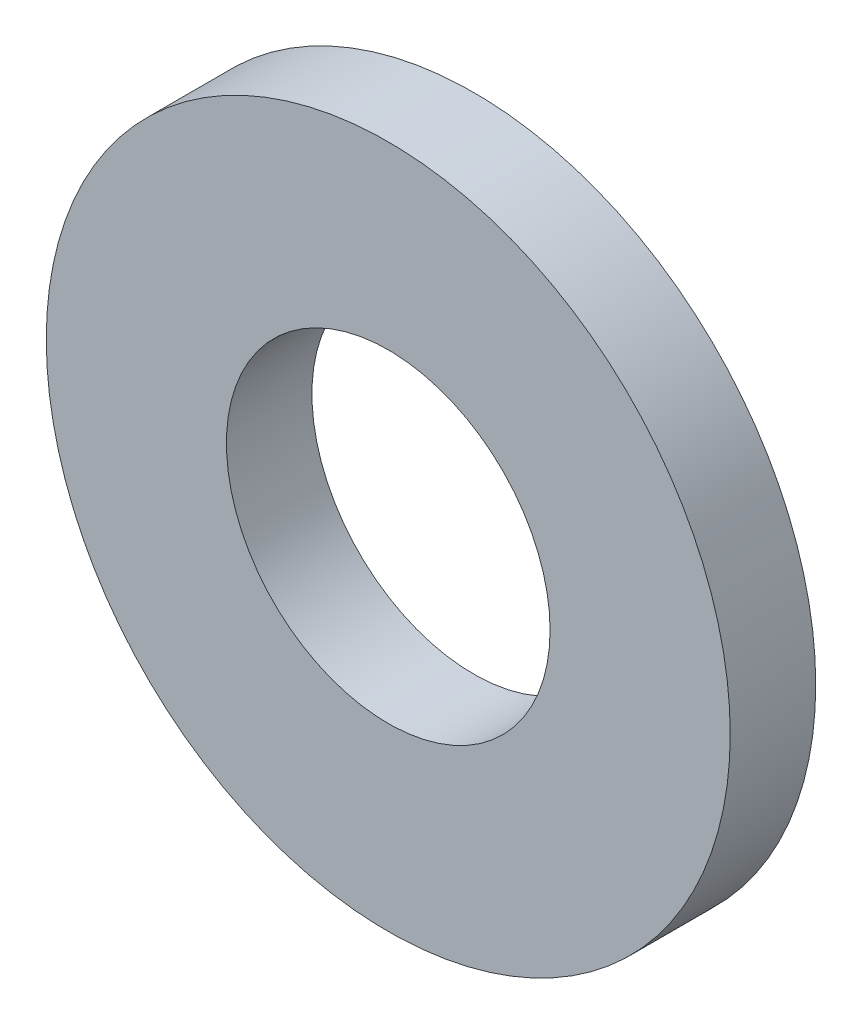
SolidWorks part; units mm, degrees
material "ПК/АБС"
ref_plane "Спереди(Плоскость XY)" through (0, 0, 0) normal (0, 0, 1) x (1, 0, 0)
ref_plane "Сверху(Плоскость XZ)" through (0, 0, 0) normal (0, 1, 0) x (1, 0, 0)
ref_plane "Справа(Плоскость ZY)" through (0, 0, 0) normal (1, 0, 0) x (0, 0, -1)
sketch "Эскиз1" plane through (0, 0, 0) normal (0, 0, 1) x (1, 0, 0)
  circle A0 centre (0, 0) radius 2.8
  circle A1 centre (0, 0) radius 1.325
  dimension "D1" = 2.65
  dimension "D2" = 5.6
extrude "Бобышка-Вытянуть1" add sketch "Эскиз1" along normal blind 0.7
